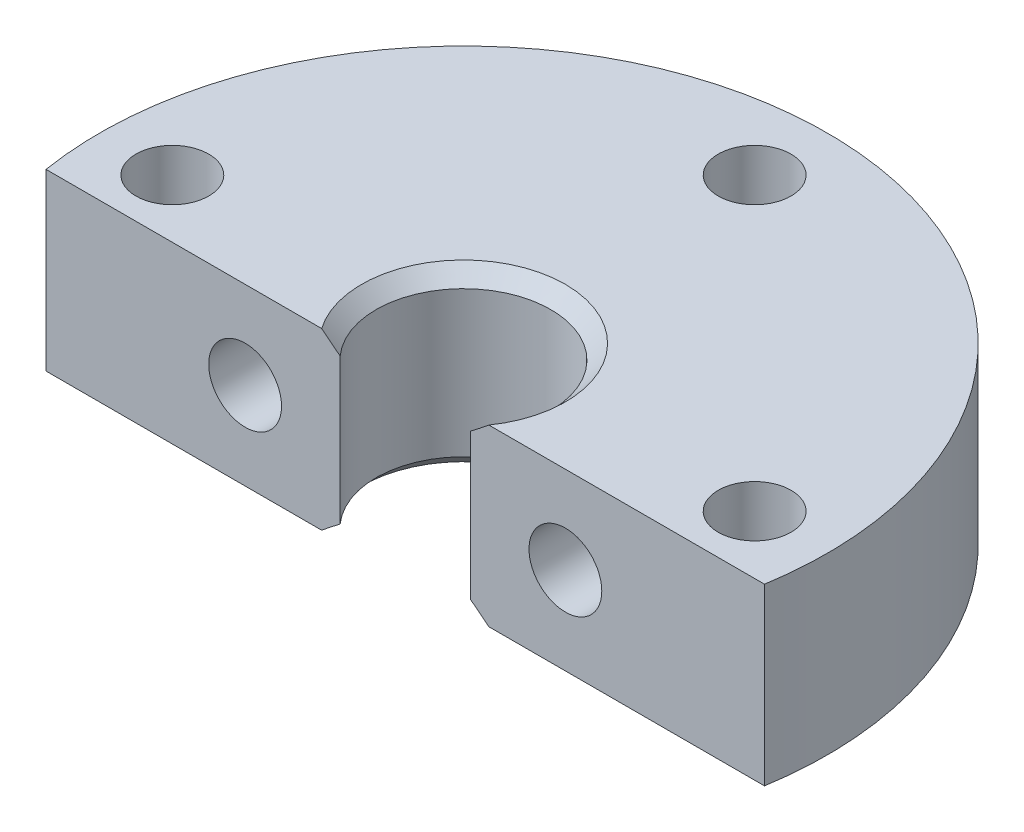
SolidWorks part; units mm, degrees
ref_plane "Front" through (0, 0, 0) normal (0, 0, 1) x (1, 0, 0)
ref_plane "Top" through (0, 0, 0) normal (0, 1, 0) x (1, 0, 0)
ref_plane "Right" through (0, 0, 0) normal (1, 0, 0) x (0, 0, -1)
sketch "草图1" plane through (0, 0, 0) normal (0, 1, 0) x (1, 0, 0)
  circle A0 centre (0, 0) radius 3
  circle A1 centre (0, 0) radius 12.5
  dimension "D1" = 25
  dimension "D2" = 6
extrude "凸台-拉伸1" add sketch "草图1" along normal mid plane 6
sketch "草图2" plane through (0, 3, 0) normal (0, 1, 0) x (1, 0, 0)
  line L0 (0, 10) -> (0, -10) construction
  line L1 (-10, 0) -> (10, 0) construction
  circle A0 centre (0, 0) radius 10 construction
  dimension "D1" = 20
hole_wizard "M3 螺纹孔2" positions "3D草图1" profile "草图3" tap size "M3" standard "GB" end condition through all
sketch3d "3D草图1"
  point P0 (0, 3, -10)
  point P3 (10, 3, 0)
  point P6 (0, 3, 10)
  point P9 (-10, 3, 0)
sketch "草图3" plane through (0, 3, -10) normal (1, 0, 0) x (0, 0, 1)
  line L0 (0, 0) -> (0, 6)
  line L1 (0, 6) -> (1.25, 6)
  line L2 (1.25, 6) -> (1.25, 0)
  line L5 (1.25, 0) -> (0, 0)
  line L11 (0, -6.35) -> (0, 107.95) construction
  dimension "通孔螺纹孔钻头直径" = 2.5
  dimension "通孔螺纹孔钻头深度" = 6
cosmetic thread "孔螺蚊线1" parameters "D2"=3
cosmetic thread "孔螺蚊线2" parameters "D2"=3
cosmetic thread "孔螺蚊线3" parameters "D2"=3
cosmetic thread "孔螺蚊线4" parameters "D2"=3
sketch "草图4" plane through (0, 3, 0) normal (0, 1, 0) x (1, 0, 0)
  line L0 (-12.339, -2) -> (12.339, -2)
  circle A0 centre (0, 0) radius 12.5 construction
  dimension "D1" = 2
extrude "切除-拉伸1" cut sketch "草图4" against normal through all and the other way through all flip side to cut
sketch "草图5" plane through (0, 0, 2) normal (0, 0, 1) x (1, 0, 0)
  line L0 (-5.5, 0) -> (5.5, 0) construction
  circle A0 centre (-5.5, 0) radius 1
  circle A1 centre (5.5, 0) radius 1
  dimension "D2" = 2
  dimension "D1" = 11
hole_wizard "M3 螺纹孔1" positions "3D草图2" profile "草图6" tap size "M3" standard "GB" end condition through all
sketch3d "3D草图2"
  point P0 (-5.5, 0, 2)
  point P3 (5.5, 0, 2)
sketch "草图6" plane through (-5.5, 0, 2) normal (1, 0, 0) x (0, -1, 0)
  line L0 (0, 0) -> (0, 14.5)
  line L1 (0, 14.5) -> (1.25, 14.5)
  line L2 (1.25, 14.5) -> (1.25, 0)
  line L5 (1.25, 0) -> (0, 0)
  line L11 (0, -6.35) -> (0, 107.95) construction
  dimension "通孔螺纹孔钻头直径" = 2.5
  dimension "通孔螺纹孔钻头深度" = 14.5
cosmetic thread "孔螺蚊线5" parameters "D2"=3
cosmetic thread "孔螺蚊线6" parameters "D2"=3
chamfer "倒角1" distance 0.5 angle 45 2 edges at (0, -3, -3) (0, 3, -3)
